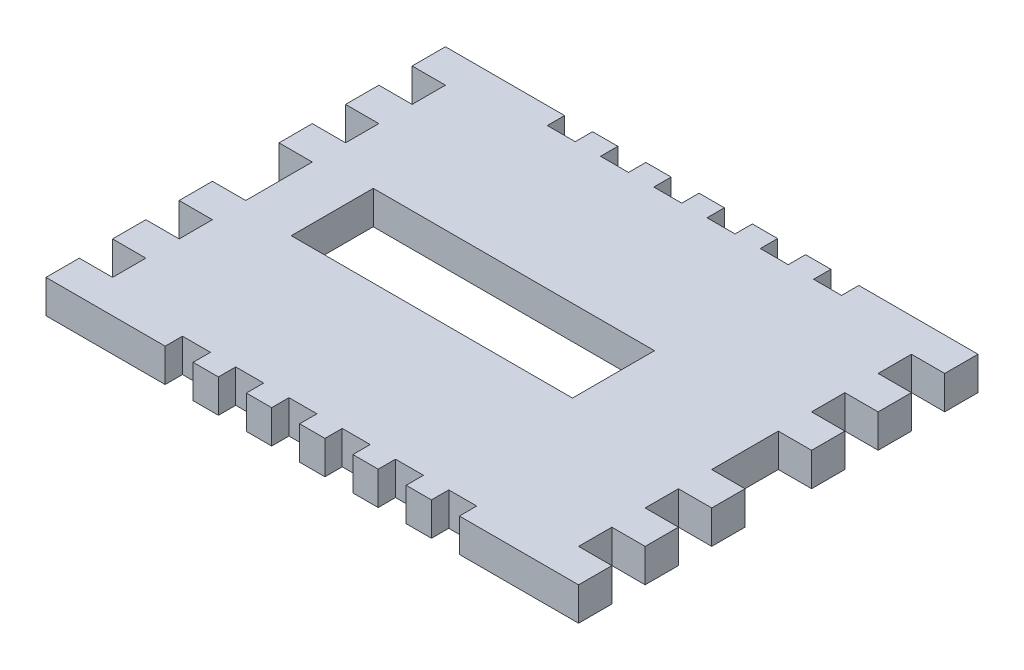
SolidWorks part; units mm, degrees
ref_plane "Front Plane" through (0, 0, 0) normal (0, 0, 1) x (1, 0, 0)
ref_plane "Top Plane" through (0, 0, 0) normal (0, 1, 0) x (1, 0, 0)
ref_plane "Right Plane" through (0, 0, 0) normal (1, 0, 0) x (0, 0, -1)
sketch "Sketch1" plane through (0, 0, 0) normal (0, 1, 0) x (1, 0, 0)
  line L1 (-44.45, -38.1) -> (44.45, -38.1)
  line L2 (-44.45, -38.1) -> (-44.45, 38.1)
  line L3 (-44.45, 38.1) -> (44.45, 38.1)
  line L4 (44.45, -38.1) -> (44.45, 38.1)
  line L5 (-44.45, -38.1) -> (44.45, 38.1) construction
  line L6 (-44.45, 38.1) -> (44.45, -38.1) construction
  line L7 (-37.465, -11) -> (22.535, -11) construction
  line L8 (-37.465, -11) -> (-37.465, 11) construction
  line L9 (-37.465, 11) -> (22.535, 11) construction
  line L10 (22.535, -11) -> (22.535, 11) construction
  line L11 (-34.29, -7.825) -> (-34.29, -11) construction
  line L12 (-34.29, -7.825) -> (19.36, -7.825)
  line L13 (-34.29, -7.825) -> (-34.29, 7.825)
  line L14 (-34.29, 7.825) -> (19.36, 7.825)
  line L15 (19.36, -7.825) -> (19.36, 7.825)
  line L16 (-37.465, -7.825) -> (-34.29, -7.825) construction
  line L17 (19.36, 7.825) -> (19.36, 11) construction
  line L18 (19.36, 7.825) -> (22.535, 7.825) construction
  point P0 (0, 0)
  point P10 (22.535, 0)
  dimension "D3" = 22
  dimension "D1" = 88.9
  dimension "D2" = 76.2
  dimension "D4" = 60
  dimension "D5" = 6.985
  dimension "D6" = 3.175
extrude "Boss-Extrude1" add sketch "Sketch1" along normal blind 6.35
sketch "Sketch2" plane through (0, 0, 0) normal (0, 1, 0) x (1, 0, 0)
  line L29 (0, 0) -> (11.4095, 0) construction
  line L35 (-28.067, -38.1) -> (-22.733, -38.1)
  line L51 (-22.733, -34.798) -> (-22.733, -38.1)
  line L52 (-28.067, -34.798) -> (-22.733, -34.798)
  line L53 (-28.067, -38.1) -> (-28.067, -34.798)
  line L91 (0, 0) -> (0, 13.7627) construction
  line L187 (-17.907, -38.1) -> (-12.573, -38.1)
  line L188 (-12.573, -34.798) -> (-12.573, -38.1)
  line L189 (-17.907, -34.798) -> (-12.573, -34.798)
  line L190 (-17.907, -38.1) -> (-17.907, -34.798)
  line L191 (-7.747, -38.1) -> (-2.413, -38.1)
  line L192 (-2.413, -34.798) -> (-2.413, -38.1)
  line L193 (-7.747, -34.798) -> (-2.413, -34.798)
  line L194 (-7.747, -38.1) -> (-7.747, -34.798)
  line L195 (2.413, -38.1) -> (7.747, -38.1)
  line L196 (7.747, -34.798) -> (7.747, -38.1)
  line L197 (2.413, -34.798) -> (7.747, -34.798)
  line L198 (2.413, -38.1) -> (2.413, -34.798)
  line L199 (12.573, -38.1) -> (17.907, -38.1)
  line L200 (17.907, -34.798) -> (17.907, -38.1)
  line L201 (12.573, -34.798) -> (17.907, -34.798)
  line L202 (12.573, -38.1) -> (12.573, -34.798)
  line L203 (22.733, -38.1) -> (28.067, -38.1)
  line L204 (28.067, -34.798) -> (28.067, -38.1)
  line L205 (22.733, -34.798) -> (28.067, -34.798)
  line L206 (22.733, -38.1) -> (22.733, -34.798)
  line L207 (22.733, 38.1) -> (22.733, 34.798)
  line L208 (22.733, 34.798) -> (28.067, 34.798)
  line L209 (28.067, 34.798) -> (28.067, 38.1)
  line L210 (22.733, 38.1) -> (28.067, 38.1)
  line L211 (12.573, 38.1) -> (12.573, 34.798)
  line L212 (12.573, 34.798) -> (17.907, 34.798)
  line L213 (17.907, 34.798) -> (17.907, 38.1)
  line L214 (12.573, 38.1) -> (17.907, 38.1)
  line L215 (2.413, 38.1) -> (2.413, 34.798)
  line L216 (2.413, 34.798) -> (7.747, 34.798)
  line L217 (7.747, 34.798) -> (7.747, 38.1)
  line L218 (2.413, 38.1) -> (7.747, 38.1)
  line L219 (-7.747, 38.1) -> (-7.747, 34.798)
  line L220 (-7.747, 34.798) -> (-2.413, 34.798)
  line L221 (-2.413, 34.798) -> (-2.413, 38.1)
  line L222 (-7.747, 38.1) -> (-2.413, 38.1)
  line L223 (-17.907, 38.1) -> (-17.907, 34.798)
  line L224 (-17.907, 34.798) -> (-12.573, 34.798)
  line L225 (-12.573, 34.798) -> (-12.573, 38.1)
  line L226 (-17.907, 38.1) -> (-12.573, 38.1)
  line L227 (-28.067, 38.1) -> (-28.067, 34.798)
  line L228 (-28.067, 34.798) -> (-22.733, 34.798)
  line L229 (-22.733, 34.798) -> (-22.733, 38.1)
  line L230 (-28.067, 38.1) -> (-22.733, 38.1)
  line L231 (44.45, 38.1) -> (-44.45, 38.1) construction
  dimension "D1" = 6
  dimension "D7" = 5.334
  dimension "D8" = 3.302
extrude "Cut-Extrude1" cut sketch "Sketch2" along normal through all
sketch "Sketch3" plane through (0, 6.35, 0) normal (0, 1, 0) x (1, 0, 0)
  line L0 (-44.45, 38.1) -> (-44.45, -38.1) construction
  line L1 (-44.45, 38.1) -> (-50.8, 38.1)
  line L2 (-44.45, 38.1) -> (-44.45, 31.75)
  line L3 (-44.45, 31.75) -> (-50.8, 31.75)
  line L4 (-50.8, 38.1) -> (-50.8, 31.75)
  line L5 (-44.45, 38.1) -> (-50.8, 31.75) construction
  line L6 (-44.45, 31.75) -> (-50.8, 38.1) construction
  line L7 (-44.45, 25.4) -> (-50.8, 25.4)
  line L8 (-44.45, 25.4) -> (-44.45, 19.05)
  line L9 (-44.45, 19.05) -> (-50.8, 19.05)
  line L10 (-50.8, 25.4) -> (-50.8, 19.05)
  line L11 (-44.45, 25.4) -> (-50.8, 19.05) construction
  line L12 (-44.45, 19.05) -> (-50.8, 25.4) construction
  line L13 (-44.45, 12.7) -> (-50.8, 12.7)
  line L14 (-44.45, 12.7) -> (-44.45, 6.35)
  line L15 (-44.45, 6.35) -> (-50.8, 6.35)
  line L16 (-50.8, 12.7) -> (-50.8, 6.35)
  line L17 (-44.45, 12.7) -> (-50.8, 6.35) construction
  line L18 (-44.45, 6.35) -> (-50.8, 12.7) construction
  line L19 (0, 0) -> (44.45, 0) construction
  line L20 (0, 0) -> (0, 38.1) construction
  line L21 (2.413, 38.1) -> (-2.413, 38.1) construction
  line L22 (44.45, -38.1) -> (44.45, 38.1) construction
  line L23 (-44.45, -6.35) -> (-50.8, -12.7) construction
  line L24 (-44.45, -12.7) -> (-50.8, -6.35) construction
  line L25 (-44.45, -19.05) -> (-50.8, -25.4) construction
  line L26 (-44.45, -25.4) -> (-50.8, -19.05) construction
  line L27 (-44.45, -31.75) -> (-50.8, -38.1) construction
  line L28 (-44.45, -38.1) -> (-50.8, -31.75) construction
  line L29 (-50.8, -12.7) -> (-50.8, -6.35)
  line L30 (-44.45, -6.35) -> (-50.8, -6.35)
  line L31 (-44.45, -12.7) -> (-44.45, -6.35)
  line L32 (-44.45, -12.7) -> (-50.8, -12.7)
  line L33 (-50.8, -25.4) -> (-50.8, -19.05)
  line L34 (-44.45, -19.05) -> (-50.8, -19.05)
  line L35 (-44.45, -25.4) -> (-44.45, -19.05)
  line L36 (-44.45, -25.4) -> (-50.8, -25.4)
  line L37 (-50.8, -38.1) -> (-50.8, -31.75)
  line L38 (-44.45, -31.75) -> (-50.8, -31.75)
  line L39 (-44.45, -38.1) -> (-44.45, -31.75)
  line L40 (-44.45, -38.1) -> (-50.8, -38.1)
  line L41 (44.45, -38.1) -> (50.8, -31.75) construction
  line L42 (44.45, -31.75) -> (50.8, -38.1) construction
  line L43 (44.45, -25.4) -> (50.8, -19.05) construction
  line L44 (44.45, -19.05) -> (50.8, -25.4) construction
  line L45 (44.45, -12.7) -> (50.8, -6.35) construction
  line L46 (44.45, -6.35) -> (50.8, -12.7) construction
  line L47 (44.45, 6.35) -> (50.8, 12.7) construction
  line L48 (44.45, 12.7) -> (50.8, 6.35) construction
  line L49 (44.45, 19.05) -> (50.8, 25.4) construction
  line L50 (44.45, 25.4) -> (50.8, 19.05) construction
  line L51 (44.45, 31.75) -> (50.8, 38.1) construction
  line L52 (44.45, 38.1) -> (50.8, 31.75) construction
  line L53 (44.45, -38.1) -> (50.8, -38.1)
  line L54 (44.45, -38.1) -> (44.45, -31.75)
  line L55 (44.45, -31.75) -> (50.8, -31.75)
  line L56 (50.8, -38.1) -> (50.8, -31.75)
  line L57 (44.45, -25.4) -> (50.8, -25.4)
  line L58 (44.45, -25.4) -> (44.45, -19.05)
  line L59 (44.45, -19.05) -> (50.8, -19.05)
  line L60 (50.8, -25.4) -> (50.8, -19.05)
  line L61 (44.45, -12.7) -> (50.8, -12.7)
  line L62 (44.45, -12.7) -> (44.45, -6.35)
  line L63 (44.45, -6.35) -> (50.8, -6.35)
  line L64 (50.8, -12.7) -> (50.8, -6.35)
  line L65 (50.8, 12.7) -> (50.8, 6.35)
  line L66 (44.45, 6.35) -> (50.8, 6.35)
  line L67 (44.45, 12.7) -> (44.45, 6.35)
  line L68 (44.45, 12.7) -> (50.8, 12.7)
  line L69 (50.8, 25.4) -> (50.8, 19.05)
  line L70 (44.45, 19.05) -> (50.8, 19.05)
  line L71 (44.45, 25.4) -> (44.45, 19.05)
  line L72 (44.45, 25.4) -> (50.8, 25.4)
  line L73 (50.8, 38.1) -> (50.8, 31.75)
  line L74 (44.45, 31.75) -> (50.8, 31.75)
  line L75 (44.45, 38.1) -> (44.45, 31.75)
  line L76 (44.45, 38.1) -> (50.8, 38.1)
  line L77 (-28.067, 38.1) -> (-44.45, 38.1) construction
  point P4 (-47.625, 34.925)
  point P13 (-47.625, 22.225)
  point P18 (-47.625, 9.525)
  point P25 (0, 38.1)
  point P29 (44.45, 0)
  point P42 (-47.625, -9.525)
  point P43 (-47.625, -22.225)
  point P44 (-47.625, -34.925)
  point P69 (47.625, -34.925)
  point P70 (47.625, -22.225)
  point P71 (47.625, -9.525)
  point P72 (47.625, 9.525)
  point P73 (47.625, 22.225)
  point P74 (47.625, 34.925)
  dimension "D1" = 6.35
  dimension "D2" = 6.35
  dimension "D3" = 12.7
  dimension "D4" = 3
extrude "Boss-Extrude2" add sketch "Sketch3" against normal up to surface (6.35 mm away) up to face at (-7.465, 0, 0)
